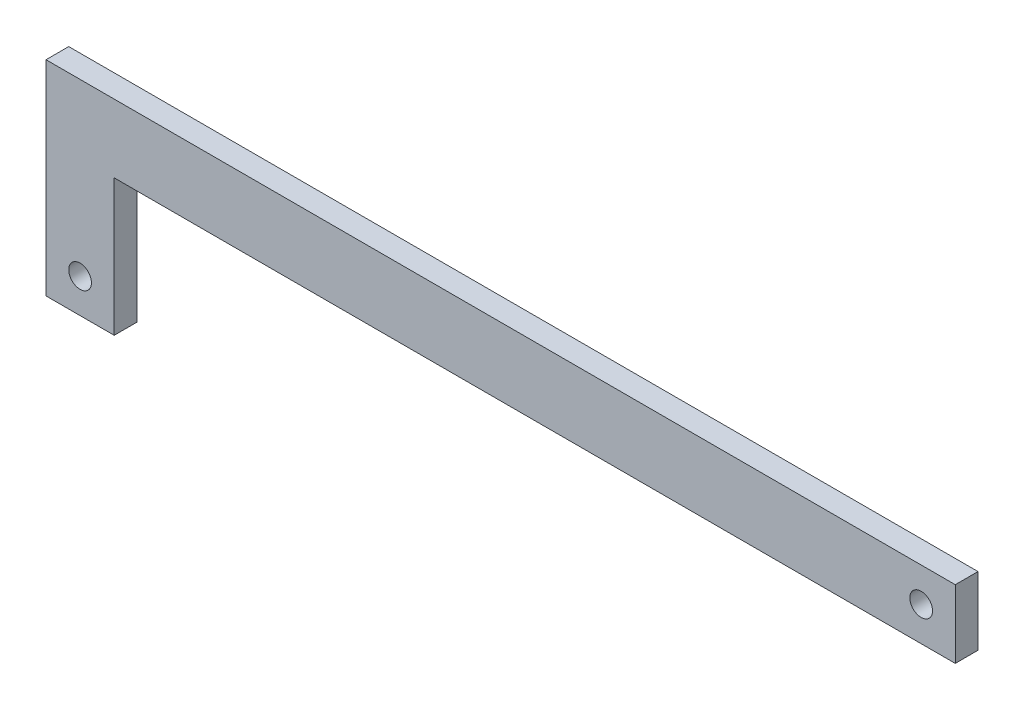
SolidWorks part; units mm, degrees
ref_plane "Front Plane" through (0, 0, 0) normal (0, 0, 1) x (1, 0, 0)
ref_plane "Top Plane" through (0, 0, 0) normal (0, 1, 0) x (1, 0, 0)
ref_plane "Right Plane" through (0, 0, 0) normal (1, 0, 0) x (0, 0, -1)
sketch "Sketch1" plane through (0, 0, 0) normal (0, 0, 1) x (1, 0, 0)
  line L0 (254, 9.525) -> (0, 9.525) construction
  line L1 (0, 0) -> (254, 0)
  line L2 (0, 0) -> (0, 19.05)
  line L3 (0, 19.05) -> (254, 19.05)
  line L4 (254, 0) -> (254, 19.05)
  line L5 (0, 0) -> (19.05, 0)
  line L6 (0, 0) -> (0, -38.1)
  line L7 (0, -38.1) -> (19.05, -38.1)
  line L8 (19.05, 0) -> (19.05, -38.1)
  line L9 (244.475, 19.05) -> (244.475, 0) construction
  line L10 (9.525, -38.1) -> (9.525, 19.05) construction
  circle A0 centre (244.475, 9.525) radius 3.175
  circle A1 centre (9.525, -28.575) radius 3.175
  dimension "D8" = 6.35
  dimension "D6" = 6.35
  dimension "D1" = 254
  dimension "D2" = 19.05
  dimension "D3" = 38.1
  dimension "D4" = 19.05
  dimension "D5" = 9.525
  dimension "D7" = 9.525
extrude "Boss-Extrude1" add sketch "Sketch1" along normal blind 6.35 contours L1 L4 L3 L2 A0 | L8 L1 L6 L7 A1
